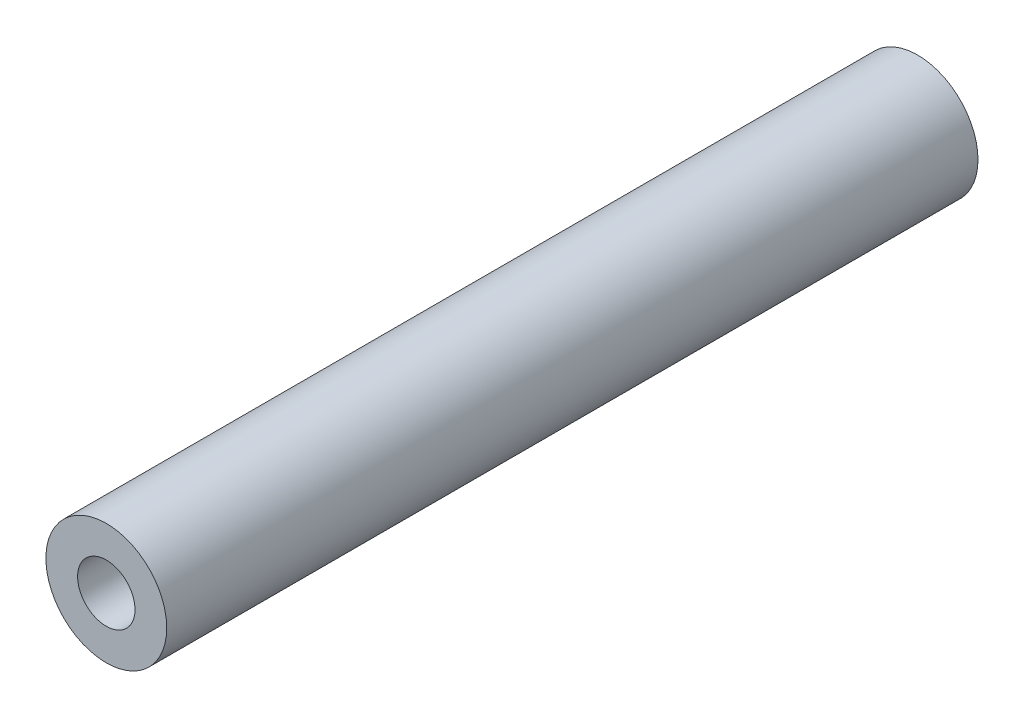
SolidWorks part; units mm, degrees
ref_plane "Front Plane" through (0, 0, 0) normal (0, 0, 1) x (1, 0, 0)
ref_plane "Top Plane" through (0, 0, 0) normal (0, 1, 0) x (1, 0, 0)
ref_plane "Right Plane" through (0, 0, 0) normal (1, 0, 0) x (0, 0, -1)
sketch "S01 - Annular section" plane through (0, 0, 0) normal (0, 0, 1) x (1, 0, 0)
  circle A0 centre (0, 0) radius 7
  circle A1 centre (0, 0) radius 3.325
  dimension "D1" = 6.65
  dimension "D2" = 14
extrude "01 - Annular section" add sketch "S01 - Annular section" along normal blind 94
